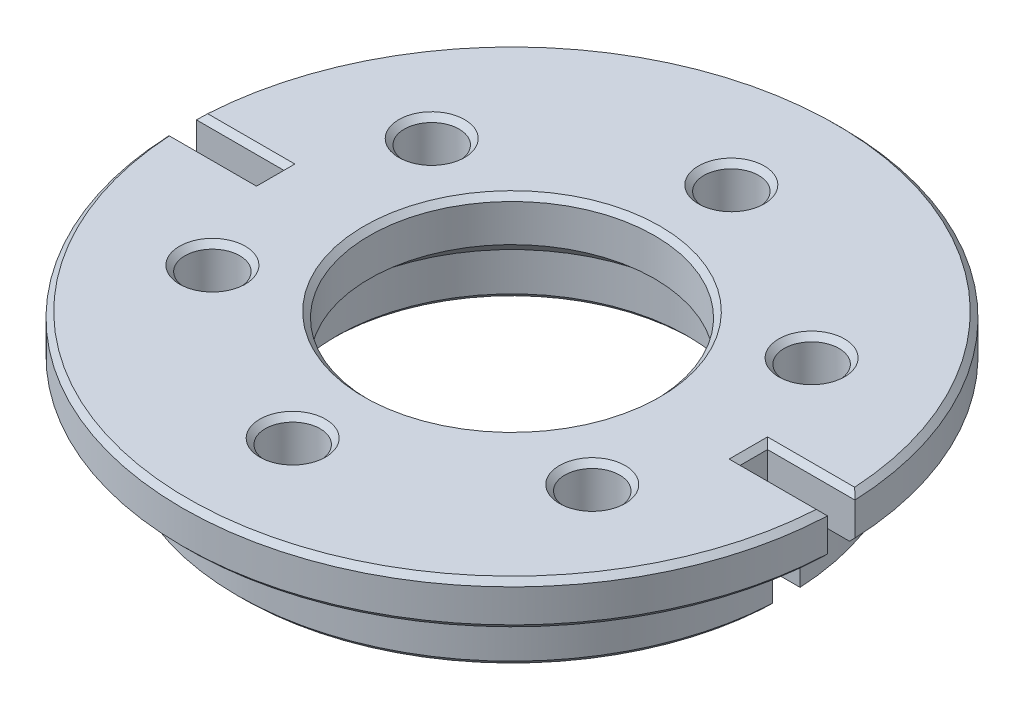
SolidWorks part; units mm, degrees
ref_plane "Front Plane" through (0, 0, 0) normal (0, 0, 1) x (1, 0, 0)
ref_plane "Top Plane" through (0, 0, 0) normal (0, 1, 0) x (1, 0, 0)
ref_plane "Right Plane" through (0, 0, 0) normal (1, 0, 0) x (0, 0, -1)
sketch "Sketch1" plane through (0, 0, 0) normal (0, 0, 1) x (1, 0, 0)
  line L0 (-15.975, 0) -> (-25.05, 0)
  line L1 (-25.05, 0) -> (-25.05, 6.4)
  line L2 (-25.05, 6.4) -> (-30.05, 6.4)
  line L3 (-30.05, 6.4) -> (-30.05, 10.4)
  line L4 (-30.05, 10.4) -> (-13, 10.4)
  line L5 (-13, 6.4963) -> (-15.975, 4)
  line L6 (-15.975, 4) -> (-15.975, 0)
  line L7 (0, 0) -> (0, 7.6896) construction
  line L8 (-13, 10.4) -> (-13, 6.4963)
  dimension "D1" = 31.95
  dimension "D2" = 50.1
  dimension "D3" = 60.1
  dimension "D4" = 50
  dimension "D5" = 6.4
  dimension "D6" = 4
  dimension "D7" = 4
  dimension "D8" = 26
revolve "Revolve1" add sketch "Sketch1" angle 360 about L7
sketch "Sketch2" plane through (0, 10.4, 0) normal (0, 1, 0) x (1, 0, 0)
  line L0 (0, 20) -> (0, 0) construction
  circle A0 centre (0, 20) radius 2.5
  circle A1 centre (17.3205, 10) radius 2.5
  circle A2 centre (17.3205, -10) radius 2.5
  circle A3 centre (0, -20) radius 2.5
  circle A4 centre (-17.3205, -10) radius 2.5
  circle A5 centre (-17.3205, 10) radius 2.5
  point P14 (0, 0)
  dimension "D2" = 5
  dimension "D3" = 20
  dimension "D1" = 6
extrude "Cut-Extrude1" cut sketch "Sketch2" against normal through all
sketch "Sketch3" plane through (0, 10.4, 0) normal (0, 1, 0) x (1, 0, 0)
  line L0 (-30.05, 0) -> (-22.05, 0)
  line L1 (0, 0) -> (0, 11.1049) construction
  line L2 (30.05, 0) -> (22.05, 0)
  circle A0 centre (0, 0) radius 30.05 construction
  dimension "D1" = 8
extrude "Cut-Extrude-Thin1" cut sketch "Sketch3" against normal through all thin thin type mid plane wall 2.5
chamfer "Chamfer1" distance 0.5 angle 45 32 edges at (0, 10.4, -13) (17.3205, 10.4, -7.5) (17.3205, 10.4, 12.5) (0, 10.4, 22.5) (-17.3205, 10.4, 12.5) (-17.3205, 10.4, -7.5) (0, 10.4, -17.5) (-26.037, 10.4, -1.25) (0, 10.4, -30.05) (26.037, 10.4, -1.25) (22.05, 10.4, 0) (26.037, 10.4, 1.25) (0, 10.4, 30.05) (-26.037, 10.4, 1.25) (-22.05, 10.4, 0) (0, 0, 25.05) (0, 6.4, 30.05) (0, 0, -25.05) (0, 6.4, -30.05) (23.5344, 0, 1.25) (22.05, 0, 0) (23.5344, 0, -1.25) (-23.5344, 0, -1.25) (-22.05, 0, 0) (-23.5344, 0, 1.25) (0, 0, -15.975) (17.3205, 0, -7.5) (17.3205, 0, 12.5) (0, 0, 22.5) (-17.3205, 0, 12.5) (-17.3205, 0, -7.5) (0, 0, -17.5)
